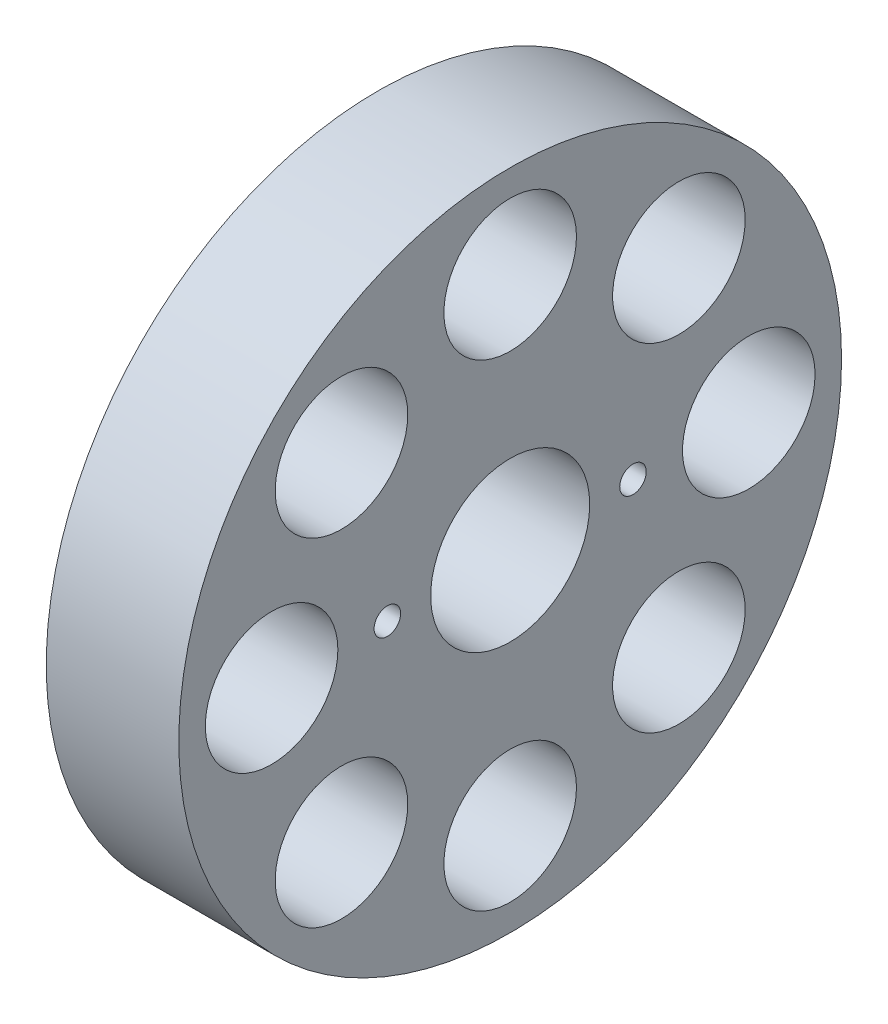
SolidWorks part; units mm, degrees
material "6061 Alloy"
ref_plane "Front Plane" through (0, 0, 0) normal (0, 0, 1) x (1, 0, 0)
ref_plane "Top Plane" through (0, 0, 0) normal (0, 1, 0) x (1, 0, 0)
ref_plane "Right Plane" through (0, 0, 0) normal (1, 0, 0) x (0, 0, -1)
sketch "Sketch1" plane through (0, 0, 0) normal (1, 0, 0) x (0, 0, -1)
  line L0 (55, 0) -> (-55, 0) construction
  line L1 (0, 55) -> (0, -55) construction
  circle A0 centre (0, 0) radius 25
  circle A1 centre (0, 18) radius 5
  circle A2 centre (12.7279, 12.7279) radius 5
  circle A3 centre (18, 0) radius 5
  circle A4 centre (12.7279, -12.7279) radius 5
  circle A5 centre (0, -18) radius 5
  circle A6 centre (-12.7279, -12.7279) radius 5
  circle A7 centre (-18, 0) radius 5
  circle A8 centre (-12.7279, 12.7279) radius 5
  circle A9 centre (0, 0) radius 6
  point P25 (0, 0)
  dimension "D2" = 50
  dimension "D3" = 10
  dimension "D4" = 18
  dimension "D5" = 12
  dimension "D1" = 8
extrude "Boss-Extrude1" add sketch "Sketch1" along normal blind 10
sketch "Sketch2" plane through (0, 0, 0) normal (-1, 0, 0) x (0, 0, 1)
  line L0 (5.5, 0) -> (-5.5, 0) construction
  line L1 (0, -5.5) -> (0, 5.5) construction
  line L2 (0, 9.8706) -> (0, -10.9505) construction
  circle A0 centre (-9.265, 0) radius 1
  circle A1 centre (9.265, 0) radius 1
  dimension "D1" = 9.265
  dimension "D2" = 2
extrude "Cut-Extrude1" cut sketch "Sketch2" against normal blind 15
